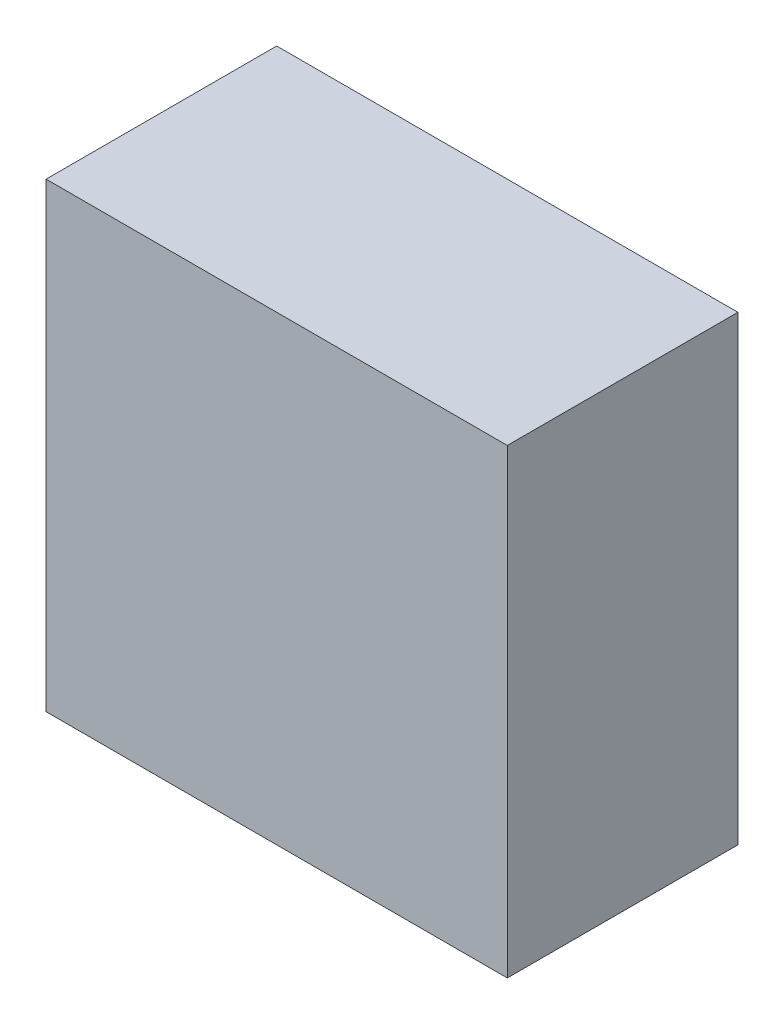
SolidWorks part; units mm, degrees
ref_plane "Plan de face" through (0, 0, 0) normal (0, 0, 1) x (1, 0, 0)
ref_plane "Plan de dessus" through (0, 0, 0) normal (0, 1, 0) x (1, 0, 0)
ref_plane "Plan de droite" through (0, 0, 0) normal (1, 0, 0) x (0, 0, -1)
sketch "Esquisse1" plane through (0, 0, 0) normal (0, 0, 1) x (1, 0, 0)
  line L0 (1, -1) -> (-1, -1)
  line L1 (-1, -1) -> (-1, 1)
  line L2 (-1, 1) -> (1, 1)
  line L3 (1, 1) -> (1, -1)
extrude "Component_Outline" add sketch "Esquisse1" along normal blind 1 separate body
sketch3d "Esquisse3D1"
  line L0 (0, 0, 0) -> (1, 0, 0)
  line L1 (0, 0, 0) -> (0, 1, 0)
  line L2 (0, 0, 0) -> (0, 0, 1)
  point P0 (0, 0, 0)
